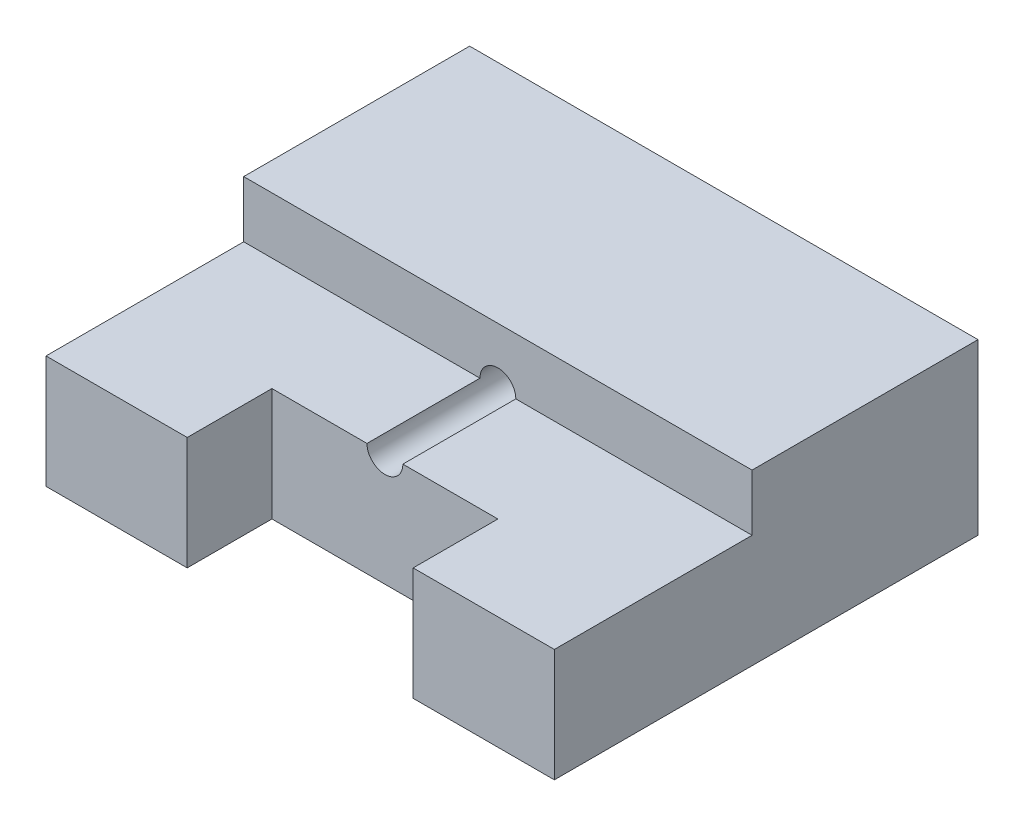
SolidWorks part; units mm, degrees
ref_plane "Front Plane" through (0, 0, 0) normal (0, 0, 1) x (1, 0, 0)
ref_plane "Top Plane" through (0, 0, 0) normal (0, 1, 0) x (1, 0, 0)
ref_plane "Right Plane" through (0, 0, 0) normal (1, 0, 0) x (0, 0, -1)
sketch "Sketch2" plane through (0, 0, 0) normal (0, 1, 0) x (1, 0, 0)
  line L1 (0, 0) -> (-18, 0)
  line L2 (0, 0) -> (0, 15)
  line L3 (0, 15) -> (-18, 15)
  line L4 (-18, 0) -> (-18, 15)
  dimension "D1" = 15
  dimension "D2" = 18
extrude "Boss-Extrude2" add sketch "Sketch2" along normal blind 6
sketch "Sketch6" plane through (0, 6, 0) normal (0, 1, 0) x (1, 0, 0)
  line L0 (0, 7) -> (0, 0)
  line L1 (-18, 0) -> (-2, 0)
  line L2 (-18, 0) -> (-18, 7)
  line L3 (-18, 7) -> (-2, 7)
  line L5 (0, 0) -> (0, 15) construction
  line L6 (0, 0) -> (-2, 0)
  line L7 (-2, 7) -> (0, 7)
  dimension "D1" = 16
  dimension "D2" = 7
extrude "Cut-Extrude3" cut sketch "Sketch6" against normal blind 2
sketch "Sketch7" plane through (0, 4, 0) normal (0, 1, 0) x (1, 0, 0)
  line L1 (-18, 0) -> (0, 0) construction
  line L3 (-13, 0) -> (-5, 0)
  line L4 (-13, 0) -> (-13, 3)
  line L5 (-13, 3) -> (-5, 3)
  line L6 (-5, 0) -> (-5, 3)
  dimension "D2" = 8
  dimension "D3" = 3
extrude "Cut-Extrude4" cut sketch "Sketch7" against normal through all
sketch "Sketch12" plane through (0, 0, -15) normal (0, 0, -1) x (-1, 0, 0)
  line L2 (9, 0) -> (9, 4) construction
  line L3 (0, 0) -> (18, 0) construction
  circle A0 centre (9, 4) radius 0.635
  dimension "D1" = 1.27
extrude "Cut-Extrude5" cut sketch "Sketch12" against normal through all contours A0
